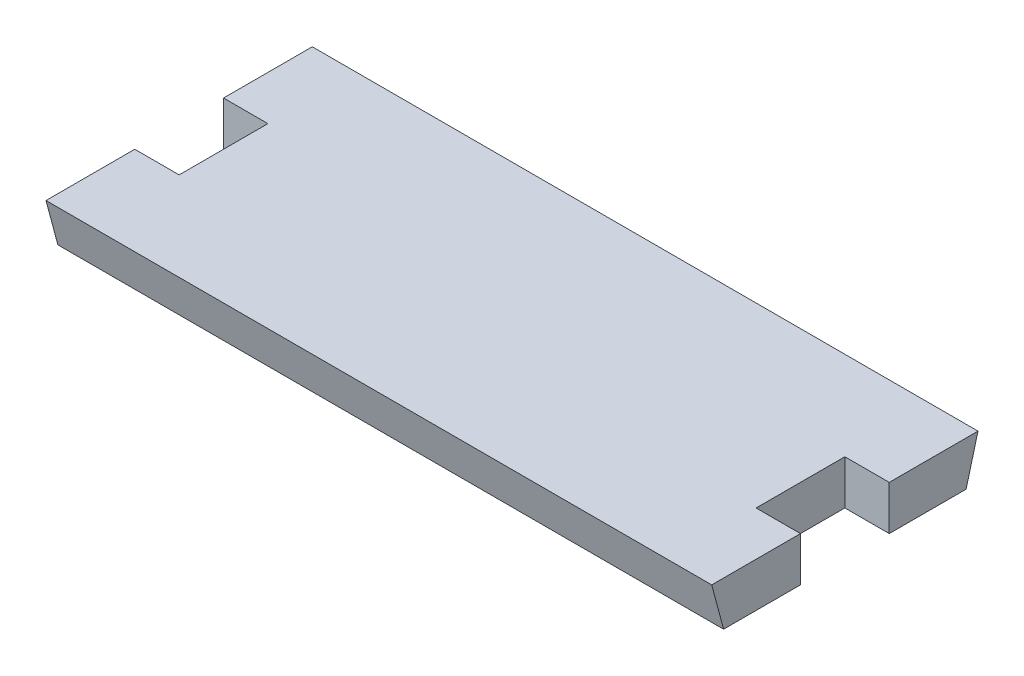
SolidWorks part; units mm, degrees
ref_plane "Front Plane" through (0, 0, 0) normal (0, 0, 1) x (1, 0, 0)
ref_plane "Top Plane" through (0, 0, 0) normal (0, 1, 0) x (1, 0, 0)
ref_plane "Right Plane" through (0, 0, 0) normal (1, 0, 0) x (0, 0, -1)
sketch "Sketch1" plane through (0, 0, 0) normal (0, 1, 0) x (1, 0, 0)
  line L1 (75, -30) -> (-75, -30)
  line L2 (75, -30) -> (75, 30)
  line L3 (75, 30) -> (-75, 30)
  line L4 (-75, -30) -> (-75, 30)
  line L5 (75, -30) -> (-75, 30) construction
  line L6 (75, 30) -> (-75, -30) construction
  point P0 (0, 0)
  dimension "D1" = 60
  dimension "D2" = 150
extrude "Boss-Extrude1" add sketch "Sketch1" along normal blind 10
draft "Draft1" type of draft neutral plane draft angle 15 faces to draft 2 face at (0, 5, -30) face at (0, 5, 30) neutral plane through (0, 10, 0) neutral plane normal (0, 1, 0) reverse direction yes parameters "D1"=15
sketch "Sketch2" plane through (0, 0, 0) normal (0, -1, 0) x (1, 0, 0)
  line L0 (-75, -10) -> (-65, -10)
  line L1 (-75, -27.3205) -> (-75, 27.3205) construction
  line L2 (-65, -10) -> (-65, 10)
  line L3 (-65, 10) -> (-75, 10)
  line L4 (-75, 10) -> (-75, -10)
  line L6 (75, -27.3205) -> (-75, -27.3205) construction
  line L7 (0, 0) -> (-75, 0) construction
  point P4 (-75, 0)
  dimension "D1" = 20
  dimension "D2" = 10
extrude "Cut-Extrude1" cut sketch "Sketch2" against normal through all
mirror "Mirror1" about plane through (0, 0, 0) normal (1, 0, 0) of "Cut-Extrude1"
